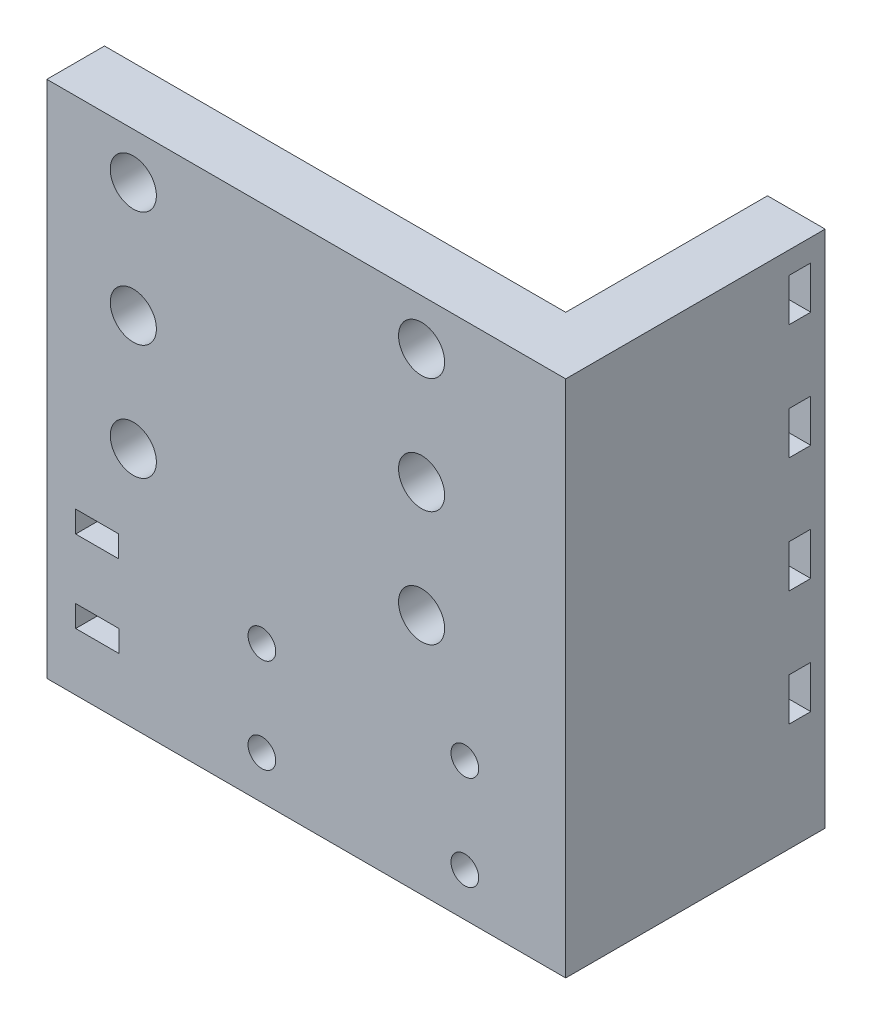
SolidWorks part; units mm, degrees
ref_plane "Front Plane" through (0, 0, 0) normal (0, 0, 1) x (1, 0, 0)
ref_plane "Top Plane" through (0, 0, 0) normal (0, 1, 0) x (1, 0, 0)
ref_plane "Right Plane" through (0, 0, 0) normal (1, 0, 0) x (0, 0, -1)
sketch "Sketch1" plane through (0, 0, 0) normal (0, 0, 1) x (1, 0, 0)
  line L1 (-57.8461, 15.6983) -> (-7.0461, 15.6983)
  line L2 (-57.8461, 15.6983) -> (-57.8461, -41.4517)
  line L3 (-57.8461, -41.4517) -> (-7.0461, -41.4517)
  line L4 (-7.0461, 15.6983) -> (-7.0461, -41.4517)
  dimension "D1" = 50.8
  dimension "D2" = 57.15
extrude "Boss-Extrude1" add sketch "Sketch1" along normal blind 6.35
sketch "Sketch5" plane through (0, 0, 6.35) normal (0, 0, 1) x (1, 0, 0)
  line L0 (-7.0461, -41.4517) -> (-7.0461, 15.6983) construction
  line L1 (-57.8461, -41.4517) -> (-7.0461, -41.4517) construction
  line L2 (-7.0461, 15.6983) -> (-57.8461, 15.6983) construction
  line L3 (-57.8461, 15.6983) -> (-57.8461, -41.4517) construction
  circle A0 centre (-11.8086, -26.2752) radius 1.524
  circle A1 centre (-11.8086, -36.6892) radius 1.524
  circle A2 centre (-34.1606, -26.2752) radius 1.524
  circle A3 centre (-34.1606, -36.6892) radius 1.524
  circle A4 centre (-48.3211, 10.6183) radius 2.54
  circle A5 centre (-16.5711, 10.6183) radius 2.54
  circle A6 centre (-48.3211, -2.0817) radius 2.54
  circle A7 centre (-16.5711, -2.0817) radius 2.54
  circle A8 centre (-48.3211, -14.7817) radius 2.54
  circle A9 centre (-16.5711, -14.7817) radius 2.54
  dimension "D1" = 4.7625
  dimension "D3" = 10.414
  dimension "D5" = 5.08
  dimension "D6" = 9.525
  dimension "D7" = 9.525
  dimension "D9" = 5.08
  dimension "D2" = 4.7625
  dimension "D4" = 22.352
  dimension "D8" = 3
extrude "Cut-Extrude1" cut sketch "Sketch5" against normal through all
sketch "Sketch6" plane through (0, 0, 6.35) normal (0, 0, 1) x (1, 0, 0)
  line L0 (-57.8461, 15.6983) -> (-57.8461, -41.4517) construction
  line L1 (-54.6711, -32.7205) -> (-49.9086, -32.7205)
  line L2 (-54.6711, -32.7205) -> (-54.6711, -35.1017)
  line L3 (-54.6711, -35.1017) -> (-49.9086, -35.1017)
  line L4 (-49.9086, -32.7205) -> (-49.9086, -35.1017)
  line L5 (-57.8461, -41.4517) -> (-7.0461, -41.4517) construction
  line L6 (-54.6711, -23.7096) -> (-49.9701, -23.7096)
  line L7 (-54.6711, -23.7096) -> (-54.6711, -26.0908)
  line L8 (-54.6711, -26.0908) -> (-49.9701, -26.0908)
  line L9 (-49.9701, -23.7096) -> (-49.9701, -26.0908)
  dimension "D1" = 4.7625
  dimension "D2" = 2.3813
  dimension "D3" = 3.175
  dimension "D4" = 6.35
  dimension "D5" = 6.6297
  dimension "D6" = 6.6297
  dimension "D7" = 3.175
extrude "Cut-Extrude2" cut sketch "Sketch6" against normal through all
sketch "Sketch7" plane through (0, 0, 6.35) normal (0, 0, 1) x (1, 0, 0)
  line L0 (-7.0461, -41.4517) -> (-7.0461, 15.6983) construction
  line L1 (-7.0461, -9.7017) -> (-57.8461, -9.7017)
  line L2 (-7.0461, -9.7017) -> (-7.0461, 15.6983)
  line L3 (-7.0461, 15.6983) -> (-57.8461, 15.6983)
  line L4 (-57.8461, -9.7017) -> (-57.8461, 15.6983)
  dimension "D1" = 25.4
extrude "Cut-Extrude3" [suppressed] cut sketch "Sketch7" against normal through all
sketch "Sketch9" plane through (-7.0461, 0, 0) normal (1, 0, 0) x (0, 0, -1)
  line L1 (-6.35, 15.6983) -> (22.225, 15.6983)
  line L2 (-6.35, 15.6983) -> (-6.35, -41.4517)
  line L3 (-6.35, -41.4517) -> (22.225, -41.4517)
  line L4 (22.225, 15.6983) -> (22.225, -41.4517)
  dimension "D1" = 28.575
extrude "Boss-Extrude2" add sketch "Sketch9" along normal blind 6.35
sketch "Sketch11" plane through (-0.6961, 0, 0) normal (1, 0, 0) x (0, 0, -1)
  line L0 (22.225, -41.4517) -> (22.225, 15.6983) construction
  line L1 (18.255, 13.2663) -> (20.6375, 13.2663)
  line L2 (18.255, 13.2663) -> (18.255, 8.5647)
  line L3 (18.255, 8.5647) -> (20.6375, 8.5647)
  line L4 (20.6375, 13.2663) -> (20.6375, 8.5647)
  line L5 (22.225, 15.6983) -> (-6.35, 15.6983) construction
  dimension "D1" = 2.3825
  dimension "D2" = 4.7015
  dimension "D3" = 1.5875
  dimension "D4" = 2.432
extrude "Cut-Extrude4" cut sketch "Sketch11" against normal through all
pattern_linear "LPattern1" count 4 spacing 12.7 along (0, -1, 0) of "Cut-Extrude4"
